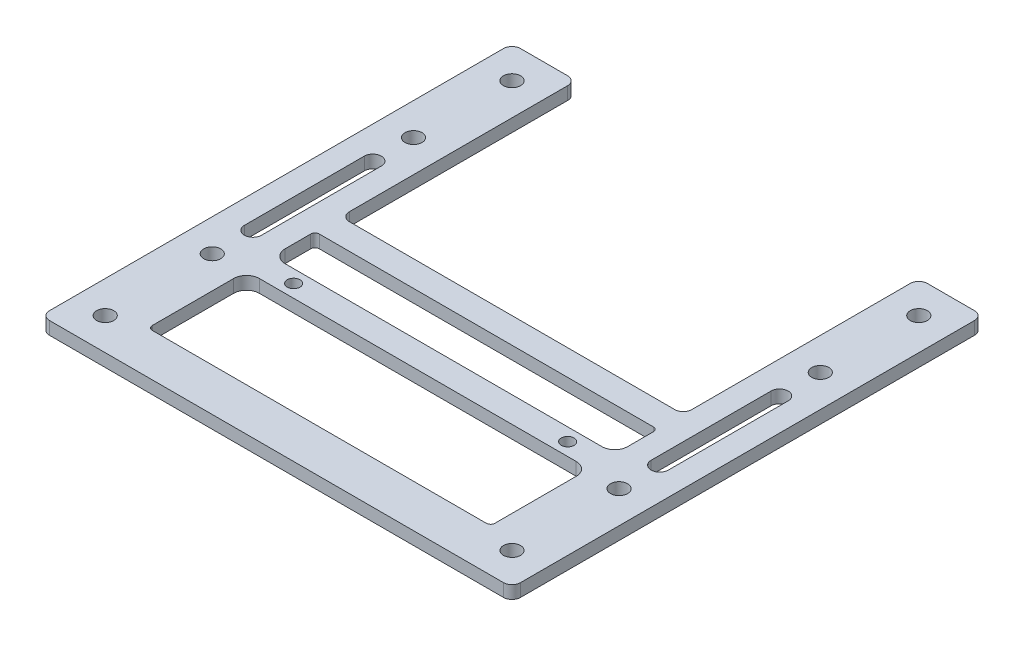
SolidWorks part; units mm, degrees
material "Thornel Mat VMA"
ref_plane "前视基准面" through (0, 0, 0) normal (0, 0, 1) x (1, 0, 0)
ref_plane "上视基准面" through (0, 0, 0) normal (0, 1, 0) x (1, 0, 0)
ref_plane "右视基准面" through (0, 0, 0) normal (1, 0, 0) x (0, 0, -1)
sketch "草图1" plane through (0, 0, 0) normal (0, 1, 0) x (1, 0, 0)
  line L0 (55, 110) -> (55, 0)
  line L2 (47.5, 7.5) -> (47.5, 110) construction
  line L5 (40, 110) -> (40, 55)
  line L9 (40, 110) -> (55, 110)
  line L11 (-55, 0) -> (55, 0)
  line L21 (40, 55) -> (-40, 55)
  line L22 (0, -1.1) -> (0, 1.1) construction
  line L23 (-47.5, 7.5) -> (-47.5, 110) construction
  line L24 (-40, 110) -> (-55, 110)
  line L25 (-40, 110) -> (-40, 55)
  line L26 (-55, 110) -> (-55, 0)
  line L27 (-32, 36) -> (32, 36) construction
  circle A0 centre (47.5, 32.5) radius 2
  circle A1 centre (47.5, 7.5) radius 2
  circle A2 centre (47.5, 79.5) radius 2
  circle A4 centre (47.5, 102.5) radius 2
  circle A5 centre (-47.5, 102.5) radius 2
  circle A6 centre (-47.5, 79.5) radius 2
  circle A7 centre (-47.5, 7.5) radius 2
  circle A8 centre (-47.5, 32.5) radius 2
  circle A9 centre (-32, 36) radius 1.5
  circle A11 centre (32, 36) radius 1.5
  dimension "D4" = 7.5
  dimension "D3" = 4
  dimension "D5" = 47
  dimension "D7" = 23
  dimension "D10" = 7.5
  dimension "D9" = 3
  dimension "D1" = 25
  dimension "D2" = 95
  dimension "D6" = 55
  dimension "D8" = 36
  dimension "D11" = 15
  dimension "D12" = 64
extrude "凸台-拉伸1" add sketch "草图1" along normal blind 3
sketch "草图2" plane through (0, 3, 0) normal (0, 1, 0) x (1, 0, 0)
  line L0 (-47.5, 70) -> (-47.5, 42) construction
  line L1 (-40, 33) -> (40, 33)
  line L2 (-40, 33) -> (-40, 10)
  line L3 (-40, 10) -> (40, 10)
  line L4 (40, 33) -> (40, 10)
  line L5 (-55, 0) -> (55, 0) construction
  line L6 (-40, 55) -> (-40, 110) construction
  line L7 (40, 110) -> (40, 55) construction
  line L8 (-40, 49) -> (-40, 39)
  line L10 (40, 49) -> (-40, 49)
  line L15 (-40, 39) -> (40, 39)
  line L16 (40, 55) -> (-40, 55) construction
  line L17 (0, -1.65) -> (0, 1.65) construction
  line L24 (40, 49) -> (40, 39)
  line L25 (-45.5, 70) -> (-45.5, 42)
  line L26 (-49.5, 70) -> (-49.5, 42)
  line L27 (-47.5, 79.5) -> (-47.5, 70) construction
  line L28 (47.5, 70) -> (47.5, 42) construction
  line L29 (45.5, 70) -> (45.5, 42)
  line L30 (49.5, 70) -> (49.5, 42)
  circle A0 centre (-32, 36) radius 1.5 construction
  arc A1 (-45.5, 70) -> (-49.5, 70) centre (-47.5, 70) ccw
  arc A2 (-49.5, 42) -> (-45.5, 42) centre (-47.5, 42) ccw
  circle A3 centre (-47.5, 79.5) radius 2 construction
  circle A4 centre (-47.5, 32.5) radius 2 construction
  arc A5 (45.5, 70) -> (49.5, 70) centre (47.5, 70) cw
  arc A6 (49.5, 42) -> (45.5, 42) centre (47.5, 42) cw
  point P12 (-47.5, 56)
  point P25 (-47.5, 72)
  point P31 (-47.5, 40)
  point P38 (47.5, 56)
  dimension "D1" = 3
  dimension "D2" = 10
  dimension "D3" = 6
  dimension "D4" = 4
  dimension "D5" = 7.5
  dimension "D6" = 6
  dimension "D7" = 7.5
extrude "切除-拉伸1" cut sketch "草图2" against normal through all
sketch "草图3" plane through (0, 3, 0) normal (0, 1, 0) x (1, 0, 0)
  line L0 (-40, 33) -> (40, 10)
  line L1 (-40, 10) -> (40, 33)
  line L2 (0, 33) -> (0, 10)
  line L3 (40, 33) -> (-40, 33) construction
  line L4 (-40, 10) -> (40, 10) construction
extrude "拉伸-薄壁2" [suppressed] add sketch "草图3" against normal up to surface (3 mm away) thin
fillet "圆角1" radius 2 8 edges at (55, 1.5, -110) (55, 1.5, 0) (-55, 1.5, 0) (-55, 1.5, -110) (-40, 1.5, -110) (-40, 1.5, -55) (40, 1.5, -55) (40, 1.5, -110)
fillet "圆角2" radius 3 4 edges at (40, 1.5, -39) (40, 1.5, -33) (-40, 1.5, -33) (-40, 1.5, -39)
fillet "圆角3" radius 1 4 edges at (40, 1.5, -10) (-40, 1.5, -10) (40, 1.5, -49) (-40, 1.5, -49)
